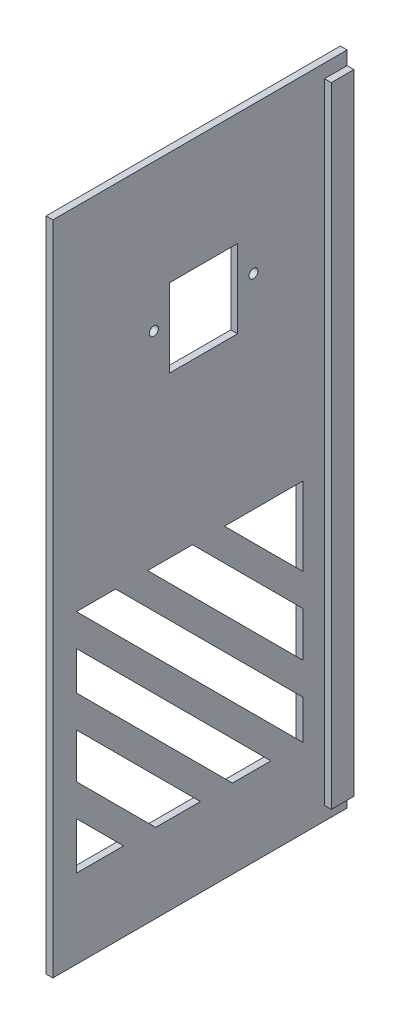
SolidWorks part; units mm, degrees
ref_plane "前视基准面" through (0, 0, 0) normal (0, 0, 1) x (1, 0, 0)
ref_plane "上视基准面" through (0, 0, 0) normal (0, 1, 0) x (1, 0, 0)
ref_plane "右视基准面" through (0, 0, 0) normal (1, 0, 0) x (0, 0, -1)
other "Configuration Table"
sketch "草图1" plane through (0, 0, 0) normal (1, 0, 0) x (0, 0, -1)
  line L1 (-36.4549, 38.9723) -> (93.5451, 38.9723)
  line L2 (-36.4549, 38.9723) -> (-36.4549, -251.0277)
  line L3 (-36.4549, -251.0277) -> (93.5451, -251.0277)
  line L4 (93.5451, 38.9723) -> (93.5451, -251.0277)
  dimension "D1" = 290
  dimension "D2" = 130
extrude "凸台-拉伸1" add sketch "草图1" along normal blind 3
sketch "草图2" plane through (0, 0, 0) normal (-1, 0, 0) x (0, 0, 1)
  line L1 (-45.1813, -10.8654) -> (-15.1813, -10.8654)
  line L2 (-45.1813, -10.8654) -> (-45.1813, -45.4054)
  line L3 (-45.1813, -45.4054) -> (-15.1813, -45.4054)
  line L4 (-15.1813, -10.8654) -> (-15.1813, -45.4054)
  dimension "D1" = 34.54
  dimension "D2" = 30
sketch "草图3" plane through (3, 0, 0) normal (1, 0, 0) x (0, 0, -1)
  line L1 (15.1813, -10.8654) -> (45.1813, -10.8654)
  line L2 (15.1813, -10.8654) -> (15.1813, -45.4054)
  line L3 (15.1813, -45.4054) -> (45.1813, -45.4054)
  line L4 (45.1813, -10.8654) -> (45.1813, -45.4054)
  dimension "D1" = 34.54
  dimension "D2" = 30
extrude "切除-拉伸3" cut sketch "草图3" against normal blind 3
sketch "草图4" plane through (3, 0, 0) normal (1, 0, 0) x (0, 0, -1)
  line L0 (15.1813, -10.8654) -> (15.1813, -45.4054) construction
  line L1 (45.1813, -45.4054) -> (45.1813, -10.8654) construction
  line L2 (15.1813, -10.8654) -> (45.1813, -10.8654)
  circle A0 centre (8.1813, -25.8654) radius 2
  circle A1 centre (52.1813, -25.8654) radius 2
  dimension "D1" = 7
  dimension "D3" = 7
  dimension "D4" = 15
  dimension "D2" = 15
extrude "切除-拉伸4" cut sketch "草图4" against normal blind 3 contours A1 | A0
sketch "草图5" plane through (0, 0, 0) normal (-1, 0, 0) x (0, 0, 1)
  line L0 (-73.9957, -150.7532) -> (-39.3637, -116.1212)
  line L1 (-73.9957, -116.1212) -> (26.0043, -116.1212)
  line L2 (-73.9957, -116.1212) -> (-73.9957, -216.1212)
  line L3 (-73.9957, -216.1212) -> (26.0043, -216.1212)
  line L4 (26.0043, -116.1212) -> (26.0043, -216.1212)
  line L5 (-73.9957, -164.8953) -> (-25.2215, -116.1212)
  line L6 (-73.9957, -184.6943) -> (-5.4226, -116.1212)
  line L7 (-73.9957, -198.8364) -> (8.7196, -116.1212)
  line L8 (-73.9957, -216.1212) -> (26.0043, -116.1212)
  line L9 (-59.8535, -216.1212) -> (26.0043, -130.2633)
  line L10 (-42.883, -216.1212) -> (26.0043, -147.2339)
  line L11 (-28.7408, -216.1212) -> (26.0043, -161.376)
  line L12 (-8.9418, -216.1212) -> (26.0043, -181.175)
  line L13 (5.2003, -216.1212) -> (26.0043, -195.3172)
  dimension "D1" = 100
  dimension "D2" = 100
  dimension "D3" = 45
  dimension "D4" = 10
  dimension "D5" = 10
  dimension "D6" = 10
  dimension "D7" = 10
  dimension "D8" = 12
  dimension "D9" = 14
  dimension "D10" = 10
  dimension "D11" = 14
extrude "切除-拉伸6" cut sketch "草图5" against normal blind 10 contours L1 L2 L0 | L2 L6 L1 L5 | L2 L8 L1 L7 | L3 L10 L4 L9 | L3 L12 L4 L11 | L13 L3 L4
sketch "草图6" plane through (3, 0, 0) normal (1, 0, 0) x (0, 0, -1)
  line L1 (93.5451, 38.9723) -> (83.5451, 38.9723)
  line L2 (93.5451, 38.9723) -> (93.5451, -251.0277)
  line L3 (93.5451, -251.0277) -> (83.5451, -251.0277)
  line L4 (83.5451, 38.9723) -> (83.5451, -251.0277)
  line L5 (-36.4549, -251.0277) -> (93.5451, -251.0277) construction
  dimension "D1" = 290
  dimension "D2" = 10
extrude "凸台-拉伸2" add sketch "草图6" along normal blind 3
sketch "草图7" plane through (0, 38.9723, 0) normal (0, 1, 0) x (1, 0, 0)
  line L1 (6, 83.5451) -> (3, 83.5451)
  line L2 (6, 83.5451) -> (6, 93.5451)
  line L3 (6, 93.5451) -> (3, 93.5451)
  line L4 (3, 83.5451) -> (3, 93.5451)
  line L5 (6, 93.5451) -> (0, 93.5451) construction
  dimension "D1" = 10
  dimension "D2" = 3
extrude "切除-拉伸7" cut sketch "草图7" against normal blind 6
sketch "草图8" plane through (0, -251.0277, 0) normal (0, -1, 0) x (1, 0, 0)
  line L1 (6, -83.5451) -> (3, -83.5451)
  line L2 (6, -83.5451) -> (6, -93.5451)
  line L3 (6, -93.5451) -> (3, -93.5451)
  line L4 (3, -83.5451) -> (3, -93.5451)
  line L5 (6, -93.5451) -> (0, -93.5451) construction
  dimension "D1" = 10
  dimension "D2" = 3
extrude "切除-拉伸8" cut sketch "草图8" against normal blind 6
